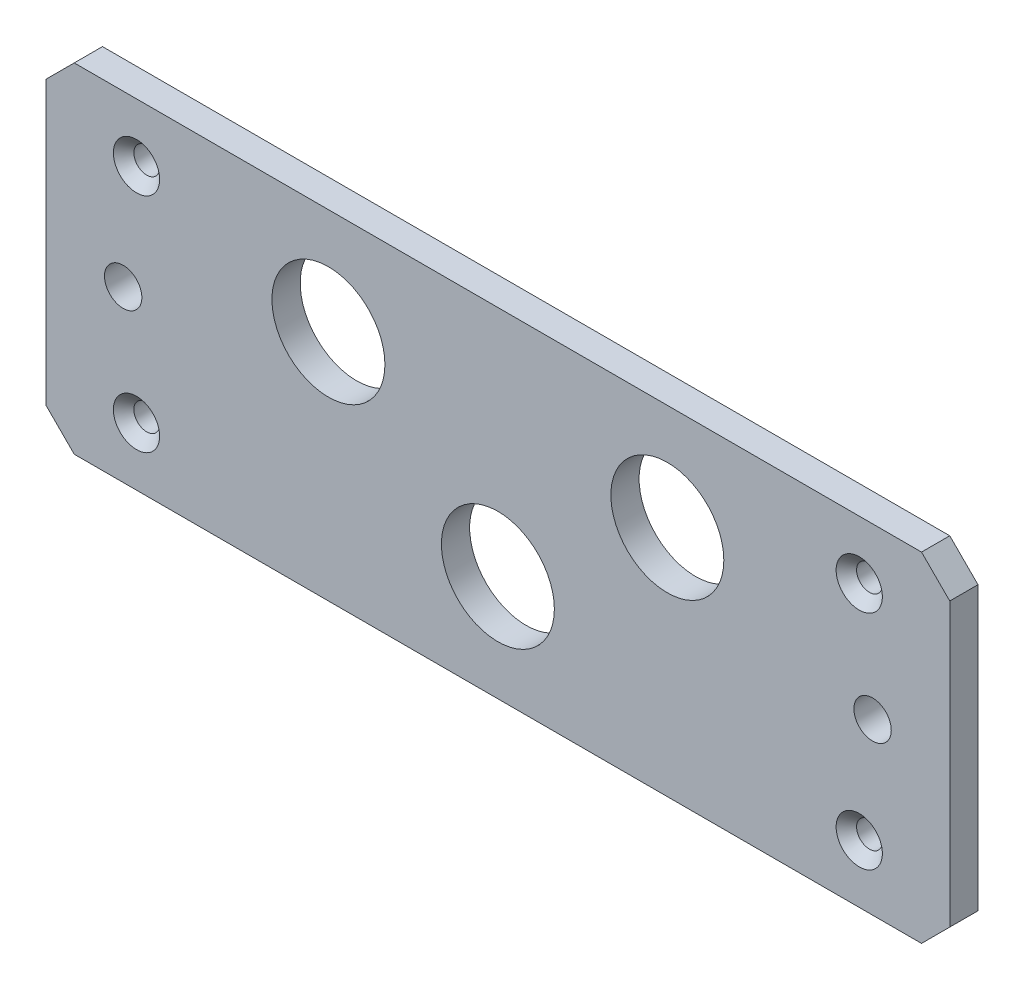
SolidWorks part; units mm, degrees
material "6061-T6 (SS)"
ref_plane "Front Plane" through (0, 0, 0) normal (0, 0, 1) x (1, 0, 0)
ref_plane "Top Plane" through (0, 0, 0) normal (0, 1, 0) x (1, 0, 0)
ref_plane "Right Plane" through (0, 0, 0) normal (1, 0, 0) x (0, 0, -1)
sketch "Sketch1" plane through (0, 0, 0) normal (0, 0, 1) x (1, 0, 0)
  line L1 (101.6, 38.1) -> (-101.6, 38.1)
  line L2 (101.6, 38.1) -> (101.6, -38.1)
  line L3 (101.6, -38.1) -> (-101.6, -38.1)
  line L4 (-101.6, 38.1) -> (-101.6, -38.1)
  line L5 (101.6, 38.1) -> (-101.6, -38.1) construction
  line L6 (101.6, -38.1) -> (-101.6, 38.1) construction
  point P0 (0, 0)
extrude "Boss-Extrude1" add sketch "Sketch1" along normal blind 6.35
hole_wizard "M8 Clearance Hole1" positions "Sketch2" profile "Sketch3" hole size "M8" standard "ANSI Metric"
sketch "Sketch2" plane through (0, 0, 6.35) normal (0, 0, 1) x (1, 0, 0)
  line L4 (0, 0) -> (0, 38.1) construction
  line L6 (-84.25, 0) -> (84.25, 0) construction
  point P17 (-84.25, 0)
  point P21 (84.25, 0)
sketch "Sketch3" plane through (84.25, 0, 6.35) normal (1, 0, 0) x (0, -1, 0)
  line L0 (0, 0) -> (0, 13.1916)
  line L1 (0, 13.1916) -> (4.2, 10.668)
  line L2 (4.2, 10.668) -> (4.2, 0)
  line L3 (4.2, 0) -> (0, 0)
  line L4 (0, 13.1916) -> (-4.2, 10.668) construction
  line L5 (0, -6.35) -> (0, 107.95) construction
  dimension "Hole Dia." = 8.4
  dimension "Hole Depth" = 10.668
  dimension "Drill Angle" = 118
chamfer "Chamfer1" distance 6.35 angle 45 4 edges at (101.6, 38.1, 3.175) (101.6, -38.1, 3.175) (-101.6, 38.1, 3.175) (-101.6, -38.1, 3.175)
hole_wizard "CSK for M5 Flat Head Machine Screw1" positions "Sketch4" profile "Sketch5" countersink size "M5" standard "ANSI Metric" end condition through all
sketch "Sketch4" plane through (0, 0, 6.35) normal (0, 0, 1) x (1, 0, 0)
  line L0 (84.25, 0) -> (84.25, 38.1) construction
  line L2 (84.25, 0) -> (81.25, 0) construction
  line L3 (81.25, 0) -> (81.25, 38.1) construction
  point P1 (81.25, 25)
  point P14 (81.25, -25)
  point P17 (-81.25, -25)
  point P18 (-81.25, 25)
sketch "Sketch5" plane through (81.25, 25, 6.35) normal (1, 0, 0) x (0, -1, 0)
  line L0 (0, 0) -> (0, 6.35)
  line L1 (0, 6.35) -> (2.9, 6.35)
  line L2 (2.9, 6.35) -> (2.9, 2.3)
  line L3 (2.9, 2.3) -> (5.2, 0)
  line L5 (5.2, 0) -> (0, 0)
  line L6 (-2.9, 2.3) -> (-5.2, 0) construction
  line L11 (0, -6.35) -> (0, 107.95) construction
  dimension "Thru Hole Dia." = 5.8
  dimension "Thru Hole Depth" = 6.35
  dimension "Near C'Sink Dia." = 10.4
  dimension "Near C'Sink Angle" = 90
hole_wizard "1 (1) Diameter Hole1" positions "Sketch6" profile "Sketch7" hole size "1" standard "ANSI Inch" end condition through all
sketch "Sketch6" plane through (0, 0, 6.35) normal (0, 0, 1) x (1, 0, 0)
  circle A0 centre (-38.1, 14.2875) radius 3.2639 construction
  circle A1 centre (0, -14.2875) radius 3.2639 construction
  circle A2 centre (38.1, 14.2875) radius 3.2639 construction
  point P0 (0, -14.2875)
  point P2 (-38.1, 14.2875)
  point P4 (38.1, 14.2875)
  point P7 (0, 0)
  point P10 (0, 0)
sketch "Sketch7" plane through (0, -14.2875, 6.35) normal (1, 0, 0) x (0, -1, 0)
  line L0 (0, 0) -> (0, 6.35)
  line L1 (0, 6.35) -> (12.7, 6.35)
  line L2 (12.7, 6.35) -> (12.7, 0)
  line L5 (12.7, 0) -> (0, 0)
  line L11 (0, -6.35) -> (0, 107.95) construction
  dimension "Thru Hole Dia." = 25.4
  dimension "Thru Hole Depth" = 6.35
